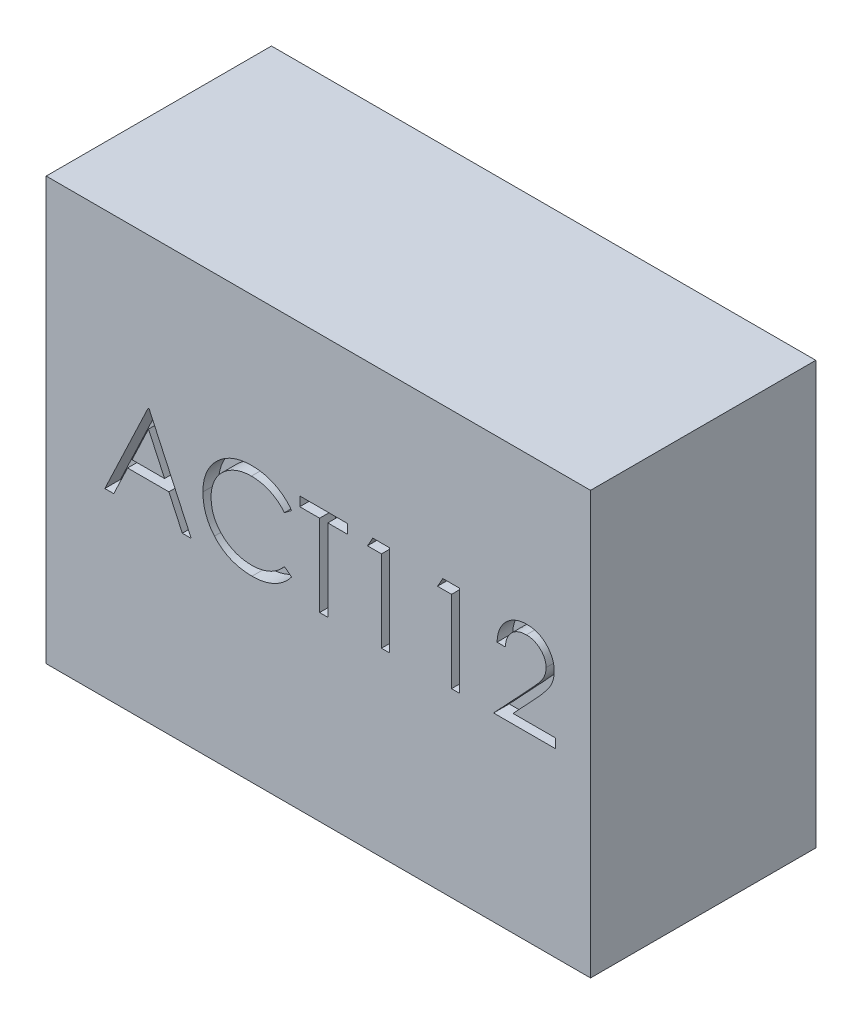
SolidWorks part; units mm, degrees
ref_plane "Front Plane" through (0, 0, 0) normal (0, 0, 1) x (1, 0, 0)
ref_plane "Top Plane" through (0, 0, 0) normal (0, 1, 0) x (1, 0, 0)
ref_plane "Right Plane" through (0, 0, 0) normal (1, 0, 0) x (0, 0, -1)
sketch "Sketch1" plane through (0, 0, 0) normal (0, 1, 0) x (1, 0, 0)
  line L1 (-8.7, -3.6) -> (8.7, -3.6)
  line L2 (-8.7, -3.6) -> (-8.7, 3.6)
  line L3 (-8.7, 3.6) -> (8.7, 3.6)
  line L4 (8.7, -3.6) -> (8.7, 3.6)
  line L5 (-8.7, -3.6) -> (8.7, 3.6) construction
  line L6 (-8.7, 3.6) -> (8.7, -3.6) construction
  point P0 (0, 0)
  dimension "D1" = 17.4
  dimension "D2" = 7.2
extrude "Boss-Extrude1" add sketch "Sketch1" along normal blind 13.5
sketch "Sketch2" plane through (0, 0, 3.6) normal (0, 0, 1) x (1, 0, 0)
  text T0 "ACT112" font "Century Gothic" height in points 11
  point P1 (-7.2674, 4.2155)
  point P2 (-8.3255, 4.46)
  point P3 (0, 0)
sketch "Sketch3" plane through (0, 0, -3.6) normal (0, 0, -1) x (-1, 0, 0)
  text T0 "ACT112" font "Century Gothic" height in points 11
extrude "Cut-Extrude1" cut sketch "Sketch3" against normal blind 0.5
extrude "Cut-Extrude2" cut sketch "Sketch2" against normal blind 0.5
